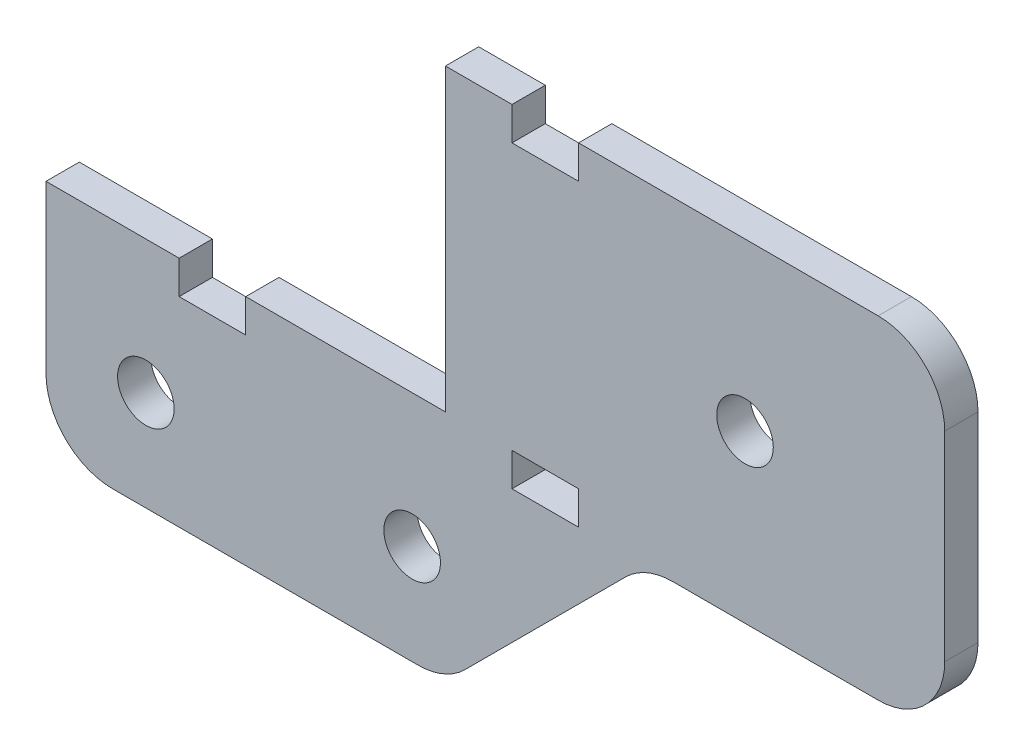
SolidWorks part; units mm, degrees
material "AISI 1020 Steel, Cold Rolled"
ref_plane "Front Plane" through (0, 0, 0) normal (1, 0, 0) x (0, 1, 0)
ref_plane "Top Plane" through (0, 0, 0) normal (0, 0, 1) x (0, 1, 0)
ref_plane "Right Plane" through (0, 0, 0) normal (0, 1, 0) x (-1, 0, 0)
sketch "Sketch1" plane through (0, 0, 0) normal (0, 0, 1) x (0, 1, 0)
  line L0 (0, 0) -> (0, 36284.5455) construction
  line L1 (-25, 50) -> (25, 50)
  line L2 (25, 50) -> (25, 40)
  line L3 (25, 40) -> (20, 40)
  line L4 (20, 40) -> (20, 30)
  line L5 (20, 30) -> (25, 30)
  line L6 (25, 30) -> (25, 20)
  line L7 (20, 35) -> (0, 35) construction
  line L8 (0, 35) -> (0, -25) construction
  line L9 (0, -25) -> (25, -25)
  line L10 (25, 20) -> (25, -25)
  line L11 (0, -25) -> (-25, -25)
  line L12 (-25, -25) -> (-55, -25) construction
  line L13 (-55, -25) -> (-55, 110) construction
  line L14 (-55, 110) -> (-20, 110)
  line L19 (-20, 110) -> (-20, 50)
  line L30 (-25, 40) -> (-25, 30)
  line L31 (-55, 110) -> (-55, 50)
  line L32 (-55, 50) -> (-25, 20)
  line L33 (-20, 110) -> (-20, 90)
  line L35 (-20, 90) -> (-25, 90)
  line L36 (-20, 90) -> (-20, 80)
  line L37 (-20, 80) -> (-25, 80)
  line L38 (-25, 90) -> (-25, 80)
  line L39 (-25, 20) -> (-25, -25)
  line L40 (-25, 30) -> (-25, 20)
  line L41 (-20, 30) -> (-25, 30)
  line L42 (-20, 40) -> (-20, 30)
  line L43 (-25, 40) -> (-20, 40)
  line L44 (-25, 50) -> (-25, 40) construction
  point P21 (28, -45)
  point P26 (28, -86)
  point P29 (0, -106)
  point P45 (0, 50)
  dimension "D1" = 25
  dimension "D2" = 10
  dimension "D3" = 10
  dimension "D4" = 5
  dimension "D5" = 50
  dimension "D6" = 25
  dimension "D7" = 60
  dimension "D8" = 30
  dimension "D9" = 135
  dimension "D10" = 60
  dimension "D11" = 35
  dimension "D12" = 20
  dimension "D13" = 5
  dimension "D14" = 10
extrude "Boss-Extrude1" add sketch "Sketch1" along normal mid plane 5
fillet "Fillet1" radius 10 5 edges at (25, 25, 0) (25, -25, 0) (-110, -55, 0) (-50, -55, 0) (-20, -25, 0)
sketch "Sketch2" plane through (0, 0, 2.5) normal (0, 0, 1) x (1, 0, 0)
  line L0 (-110, -25) -> (-15.8579, -25)
  line L1 (-110, -45) -> (-110, -20) construction
  line L2 (-47.0711, -52.0711) -> (-22.9289, -27.9289) construction
  line L3 (-100, -55) -> (-54.1421, -55) construction
  line L4 (-47.0711, -52.0711) -> (-22.9289, -27.9289)
  line L5 (-100, -55) -> (-54.1421, -55)
  line L6 (-110, -45) -> (-110, -25)
  line L7 (-110, -25) -> (-110, -20) construction
  line L8 (-15.8579, -25) -> (15, -25) construction
  line L9 (-35, -40) -> (-110, -40) construction
  line L10 (-35, -40) -> (-55, -40) construction
  line L11 (-35, -40) -> (-95, -40) construction
  line L12 (-35, 20) -> (-35, -20) construction
  line L13 (-40, 20) -> (-30, 20) construction
  line L14 (-40, -20) -> (-30, -20) construction
  line L15 (-35, 0) -> (25, 0) construction
  line L16 (25, 15) -> (25, -15) construction
  arc A0 (-54.1421, -55) -> (-47.0711, -52.0711) centre (-54.1421, -45) ccw construction
  arc A1 (-110, -45) -> (-100, -55) centre (-100, -45) ccw construction
  arc A2 (-54.1421, -55) -> (-47.0711, -52.0711) centre (-54.1421, -45) ccw
  arc A3 (-110, -45) -> (-100, -55) centre (-100, -45) ccw
  arc A4 (-15.8579, -25) -> (-22.9289, -27.9289) centre (-15.8579, -35) ccw construction
  arc A5 (-15.8579, -25) -> (-22.9289, -27.9289) centre (-15.8579, -35) ccw
  circle A6 centre (-95, -40) radius 4.25
  circle A7 centre (-55, -40) radius 4.25
  circle A8 centre (-5, 0) radius 4.25
  dimension "D3" = 8.5
  dimension "D4" = 8.5
  dimension "D1" = 20
  dimension "D2" = 40
extrude "Cut-Extrude1" cut sketch "Sketch2" against normal up to next contours A6 | A7 | A8
